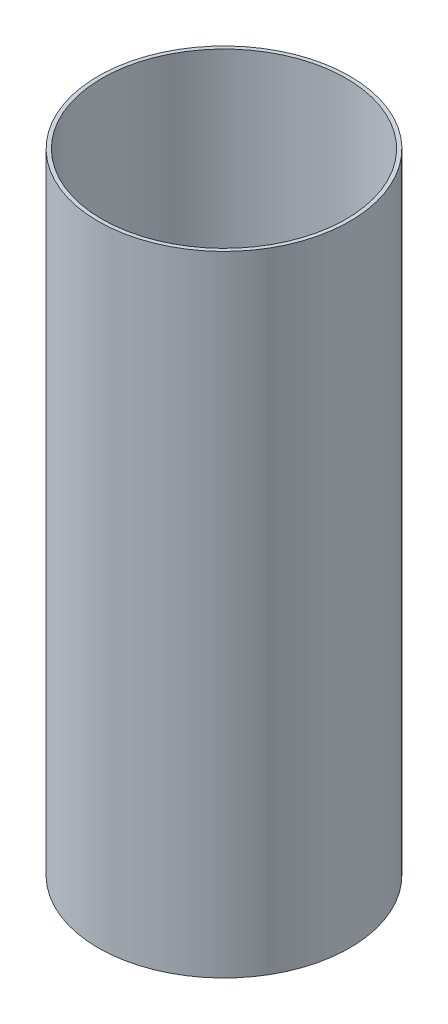
SolidWorks part; units mm, degrees
ref_plane "Front Plane" through (0, 0, 0) normal (0, 0, 1) x (1, 0, 0)
ref_plane "Top Plane" through (0, 0, 0) normal (0, 1, 0) x (1, 0, 0)
ref_plane "Right Plane" through (0, 0, 0) normal (1, 0, 0) x (0, 0, -1)
sketch "Sketch1" plane through (0, 0, 0) normal (0, 1, 0) x (1, 0, 0)
  circle A0 centre (0, 0) radius 76.1746
  circle A1 centre (0, 0) radius 73.914
  dimension "D1" = 152.3492
  dimension "D2" = 147.828
extrude "Boss-Extrude1" add sketch "Sketch1" along normal blind 381
